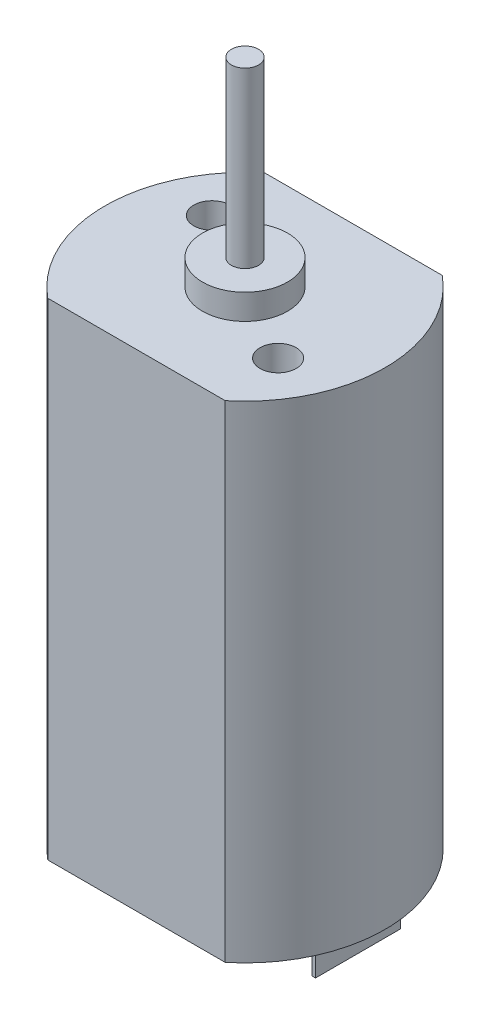
SolidWorks part; units mm, degrees
ref_plane "Front Plane" through (0, 0, 0) normal (0, 0, 1) x (1, 0, 0)
ref_plane "Top Plane" through (0, 0, 0) normal (0, 1, 0) x (1, 0, 0)
ref_plane "Right Plane" through (0, 0, 0) normal (1, 0, 0) x (0, 0, -1)
sketch "Sketch1" plane through (0, 0, 0) normal (0, 1, 0) x (1, 0, 0)
  line L0 (-4.9054, 6) -> (4.9054, 6)
  line L1 (4.9054, -6) -> (-4.9054, -6)
  arc A0 (-4.9054, 6) -> (-4.9054, -6) centre (0, 0) ccw
  arc A1 (4.9054, -6) -> (4.9054, 6) centre (0, 0) ccw
  dimension "D1" = 7.75
  dimension "D2" = 12
extrude "Boss-Extrude1" add sketch "Sketch1" along normal mid plane 26.9
sketch "Sketch2" plane through (0, 13.45, 0) normal (0, 1, 0) x (1, 0, 0)
  circle A0 centre (0, 0) radius 2.35
  dimension "D1" = 4.7
extrude "Boss-Extrude2" add sketch "Sketch2" along normal blind 1.4
sketch "Sketch3" plane through (0, 14.85, 0) normal (0, 1, 0) x (1, 0, 0)
  circle A0 centre (0, 0) radius 0.75
  dimension "D1" = 1.5
extrude "Boss-Extrude5" add sketch "Sketch3" along normal blind 9.6
sketch "Sketch4" plane through (0, -13.45, 0) normal (0, -1, 0) x (1, 0, 0)
  line L0 (-6.05, 0) -> (6.05, 0) construction
  line L1 (-6.25, 2.35) -> (-6.05, 2.35)
  line L2 (-6.25, 2.35) -> (-6.25, -2.35)
  line L3 (-6.25, -2.35) -> (-6.05, -2.35)
  line L4 (-6.05, 2.35) -> (-6.05, -2.35)
  line L5 (6.05, 2.35) -> (6.25, 2.35)
  line L6 (6.05, 2.35) -> (6.05, -2.35)
  line L7 (6.05, -2.35) -> (6.25, -2.35)
  line L8 (6.25, 2.35) -> (6.25, -2.35)
  dimension "D1" = 0.2
  dimension "D2" = 12.1
  dimension "D3" = 4.7
extrude "Boss-Extrude6" add sketch "Sketch4" along normal blind 1.9
sketch "Sketch5" plane through (0, 13.45, 0) normal (0, 1, 0) x (1, 0, 0)
  line L0 (-4.3301, 2.5) -> (4.3301, -2.5) construction
  line L1 (0, 0) -> (-5.6857, 0) construction
  circle A0 centre (-4.3301, 2.5) radius 1
  circle A1 centre (4.3301, -2.5) radius 1
  dimension "D3" = 2
  dimension "D1" = 30
  dimension "D2" = 10
extrude "Cut-Extrude1" cut sketch "Sketch5" against normal blind 1.9
